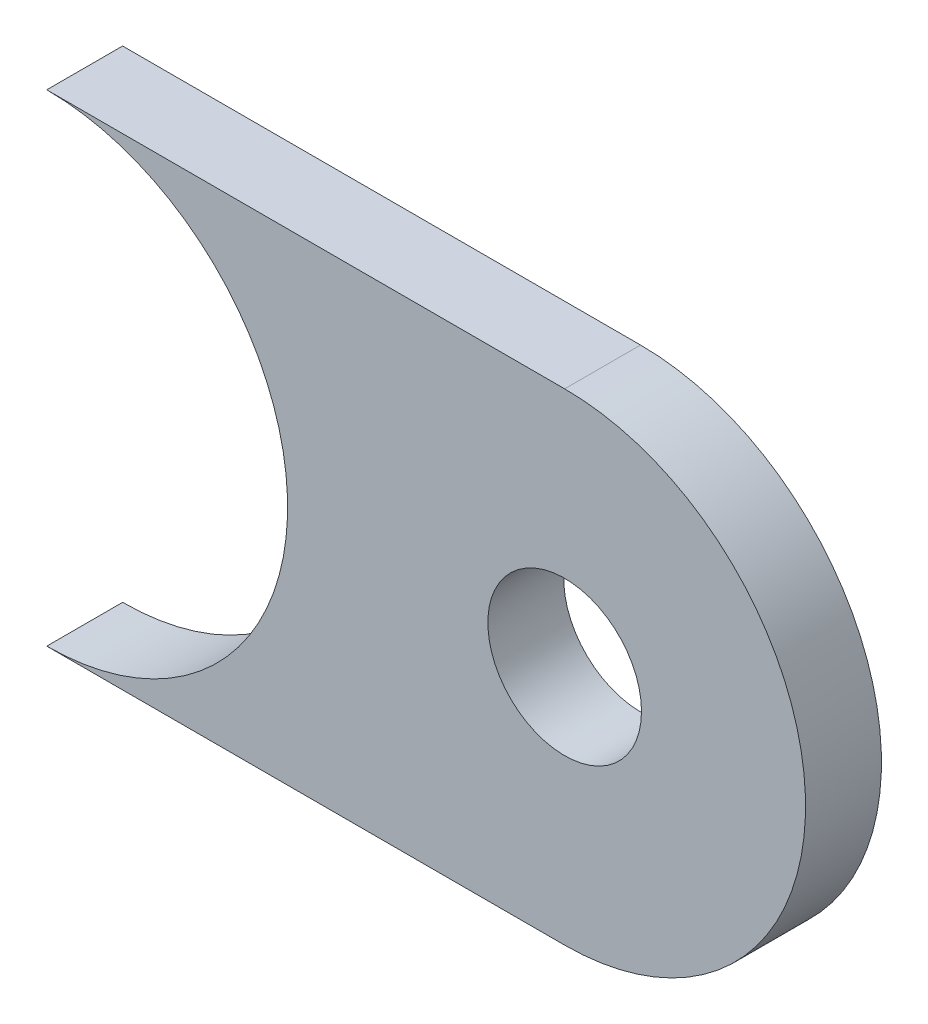
SolidWorks part; units mm, degrees
ref_plane "Front Plane" through (0, 0, 0) normal (0, 0, 1) x (1, 0, 0)
ref_plane "Top Plane" through (0, 0, 0) normal (0, 1, 0) x (1, 0, 0)
ref_plane "Right Plane" through (0, 0, 0) normal (1, 0, 0) x (0, 0, -1)
sketch "Sketch1" plane through (0, 0, 0) normal (0, 0, 1) x (1, 0, 0)
  line L0 (0, 0) -> (27.305, 0) construction
  line L1 (0, 12.7) -> (27.305, 12.7)
  line L2 (0, -12.7) -> (27.305, -12.7)
  circle A0 centre (27.305, 0) radius 4.05
  arc A1 (27.305, -12.7) -> (27.305, 12.7) centre (27.305, 0) ccw
  arc A2 (0, -12.7) -> (0, 12.7) centre (0, 0) ccw
  dimension "D2" = 8.1
  dimension "D3" = 25.4
  dimension "D4" = 25.4
  dimension "D1" = 27.305
  dimension "D5" = 27.305
extrude "Boss-Extrude1" add sketch "Sketch1" along normal blind 4
